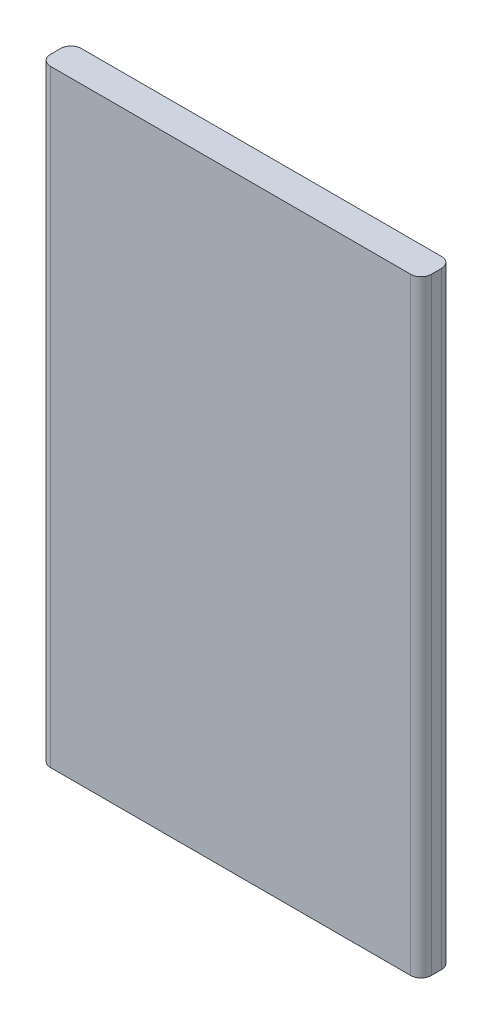
SolidWorks part; units mm, degrees
ref_plane "Front Plane" through (0, 0, 0) normal (0, 0, 1) x (1, 0, 0)
ref_plane "Top Plane" through (0, 0, 0) normal (0, 1, 0) x (1, 0, 0)
ref_plane "Right Plane" through (0, 0, 0) normal (1, 0, 0) x (0, 0, -1)
sketch "Sketch1" plane through (0, 0, 0) normal (0, 0, 1) x (1, 0, 0)
  line L1 (-18.5, -29.5) -> (18.5, -29.5)
  line L2 (-18.5, -29.5) -> (-18.5, 29.5)
  line L3 (-18.5, 29.5) -> (18.5, 29.5)
  line L4 (18.5, -29.5) -> (18.5, 29.5)
  line L5 (-18.5, -29.5) -> (18.5, 29.5) construction
  line L6 (-18.5, 29.5) -> (18.5, -29.5) construction
  point P0 (0, 0)
  dimension "D1" = 59
  dimension "D2" = 37
extrude "Boss-Extrude1" add sketch "Sketch1" along normal blind 3
fillet "Fillet1" radius 1 4 edges at (18.5, 0, 0) (-18.5, 0, 0) (-18.5, 0, 3) (18.5, 0, 3)
